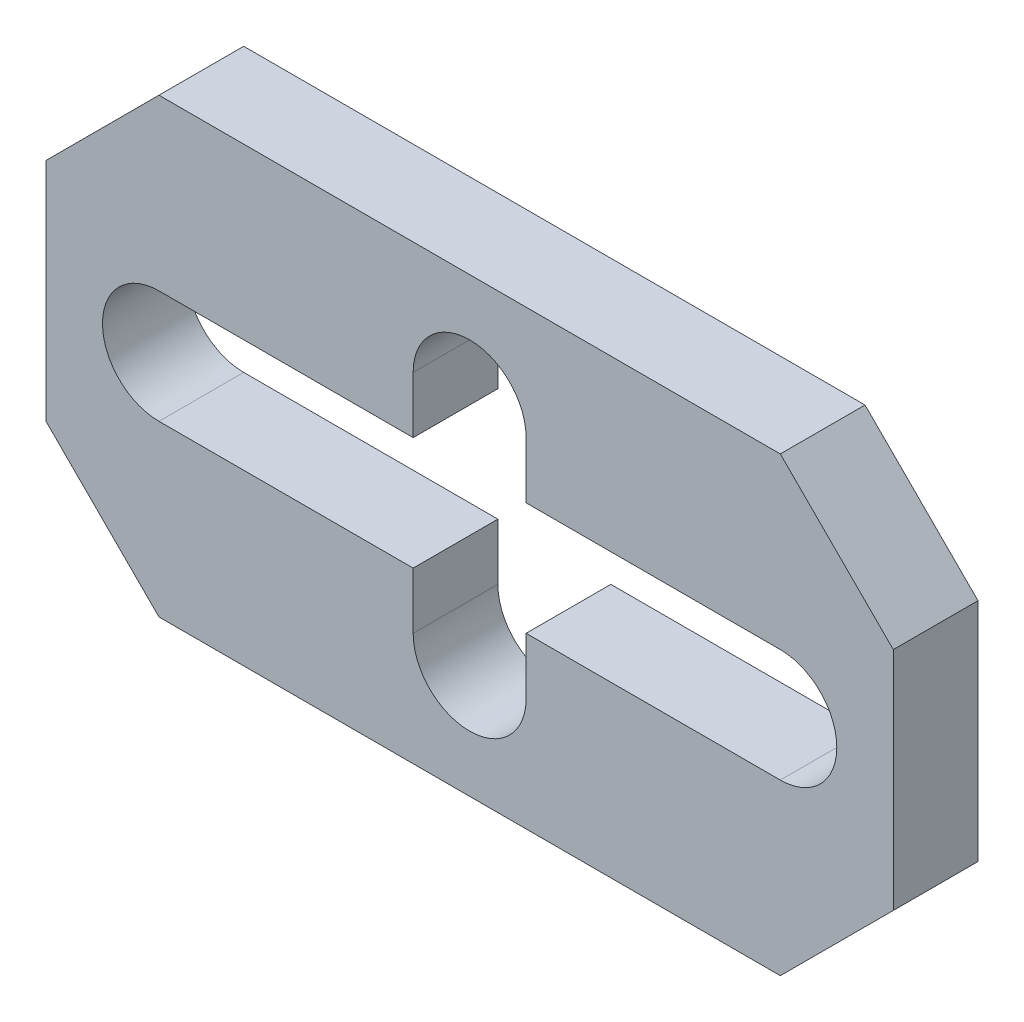
SolidWorks part; units mm, degrees
ref_plane "Front Plane" through (0, 0, 0) normal (0, 0, 1) x (1, 0, 0)
ref_plane "Top Plane" through (0, 0, 0) normal (0, 1, 0) x (1, 0, 0)
ref_plane "Right Plane" through (0, 0, 0) normal (1, 0, 0) x (0, 0, -1)
sketch "Sketch1" plane through (0, 0, 0) normal (0, 0, 1) x (1, 0, 0)
  line L0 (-75, 20) -> (-55, 40)
  line L1 (-55, -40) -> (55, -40)
  line L2 (-75, -20) -> (-75, 20)
  line L3 (-55, 40) -> (55, 40)
  line L4 (75, -20) -> (75, 20)
  line L5 (-55, -40) -> (-75, -20)
  line L6 (55, -40) -> (75, -20)
  line L7 (55, 40) -> (75, 20)
  line L8 (-10, 10) -> (-10, 20)
  line L10 (-10, -20) -> (-10, -10)
  line L12 (10, -20) -> (10, -10)
  line L13 (-55, -10) -> (-10, -10)
  line L15 (-55, 10) -> (-10, 10)
  line L17 (10, 10) -> (55, 10)
  line L18 (10, -10) -> (55, -10)
  line L19 (10, 10) -> (10, 20)
  arc A0 (10, 20) -> (-10, 20) centre (0, 20) ccw
  arc A1 (-10, -20) -> (10, -20) centre (0, -20) ccw
  arc A2 (55, -10) -> (55, 10) centre (55, 0) ccw
  arc A3 (-55, 10) -> (-55, -10) centre (-55, 0) ccw
  point P0 (0, 0)
  point P1 (75, 40)
  point P2 (-75, -40)
  point P3 (-75, 40)
  point P4 (75, -40)
  point P14 (0, 0)
  point P20 (0, 0)
  dimension "D1" = 20
  dimension "D2" = 150
  dimension "D3" = 80
  dimension "D4" = 40
  dimension "D5" = 110
  dimension "D10" = 20
extrude "Boss-Extrude1" add sketch "Sketch1" along normal blind 15
